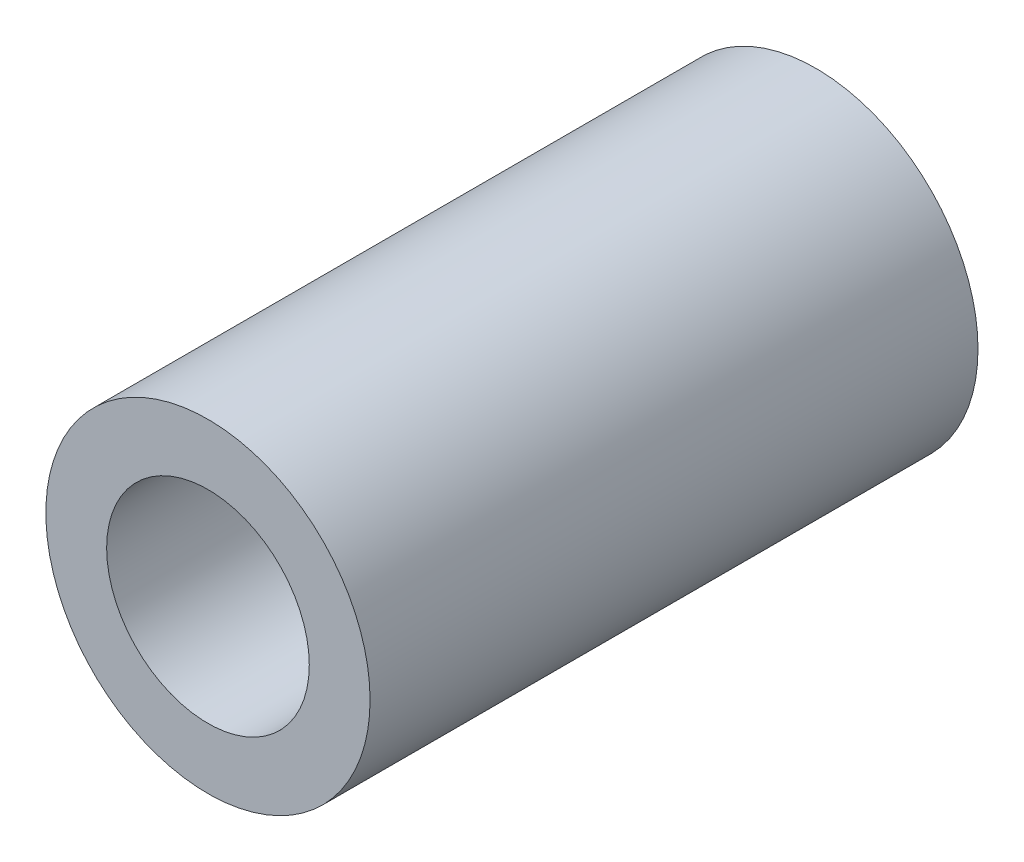
SolidWorks part; units mm, degrees
ref_plane "前视基准面" through (0, 0, 0) normal (0, 0, 1) x (1, 0, 0)
ref_plane "上视基准面" through (0, 0, 0) normal (0, 1, 0) x (1, 0, 0)
ref_plane "右视基准面" through (0, 0, 0) normal (1, 0, 0) x (0, 0, -1)
sketch "草图1" plane through (0, 0, 0) normal (0, 0, 1) x (1, 0, 0)
  circle A0 centre (0, 0) radius 1
  circle A1 centre (0, 0) radius 1.6
extrude "凸台-拉伸1" add sketch "草图1" along normal blind 6
